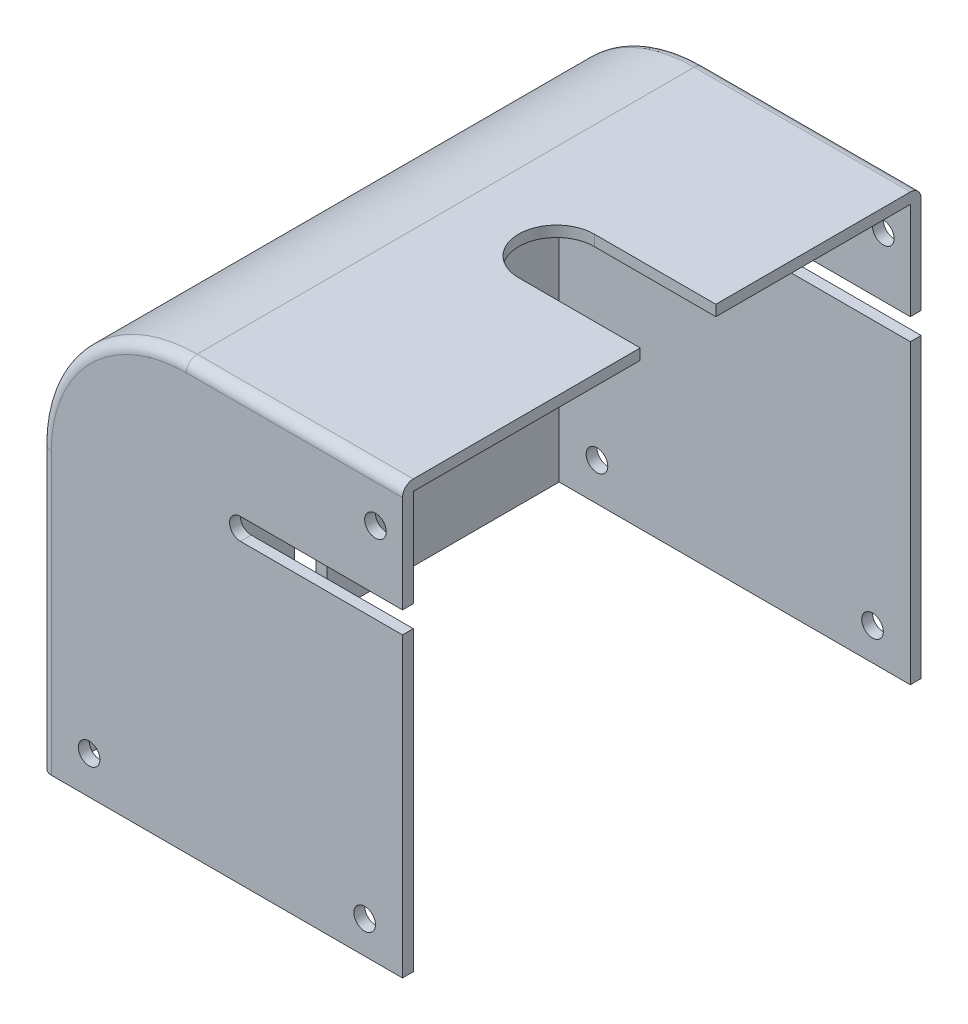
SolidWorks part; units mm, degrees
ref_plane "Front Plane" through (0, 0, 0) normal (0, 0, 1) x (1, 0, 0)
ref_plane "Top Plane" through (0, 0, 0) normal (0, 1, 0) x (1, 0, 0)
ref_plane "Right Plane" through (0, 0, 0) normal (1, 0, 0) x (0, 0, -1)
sketch "Sketch1" plane through (0, 0, 0) normal (0, 0, 1) x (1, 0, 0)
  line L0 (0, 0) -> (-40, 0)
  line L1 (-65, -25) -> (-65, -77)
  line L2 (0, 2) -> (-40, 2)
  line L3 (-67, -25) -> (-67, -77)
  line L4 (0, 0) -> (0, 2)
  line L5 (-65, -77) -> (-67, -77)
  arc A0 (-40, 0) -> (-65, -25) centre (-40, -25) ccw
  arc A1 (-40, 2) -> (-67, -25) centre (-40, -25) ccw
  dimension "D1" = 25
  dimension "D2" = 65
  dimension "D3" = 77
  dimension "D4" = 2
extrude "Boss-Extrude1" add sketch "Sketch1" along normal mid plane 92
sketch "Sketch2" plane through (0, 0, 46) normal (0, 0, 1) x (1, 0, 0)
  line L0 (-67, -25) -> (-67, -77) construction
  line L1 (0, 2) -> (-40, 2) construction
  line L2 (-67, -25) -> (-67, -77)
  line L3 (0, 2) -> (-40, 2)
  line L4 (-67, -77) -> (0, -77)
  line L5 (0, -77) -> (0, 2)
  arc A0 (-40, 2) -> (-67, -25) centre (-40, -25) ccw construction
  arc A1 (-40, 2) -> (-67, -25) centre (-40, -25) ccw
extrude "Boss-Extrude2" add sketch "Sketch2" along normal blind 2
mirror "Mirror1" about plane through (0, 0, 0) normal (0, 0, 1) of "Boss-Extrude2"
fillet "Fillet1" radius 2 6 edges at (-67, -51, -48) (-59.0919, -5.9081, -48) (-20, 2, -48) (-67, -51, 48) (-59.0919, -5.9081, 48) (-20, 2, 48)
sketch "Sketch3" plane through (-67, 0, 0) normal (-1, 0, 0) x (0, 0, 1)
  line L0 (0, -77) -> (0, -47) construction
  line L1 (46, -77) -> (-46, -77) construction
  line L2 (-3, -77) -> (-3, -47)
  line L3 (3, -77) -> (3, -47)
  arc A0 (-3, -77) -> (3, -77) centre (0, -77) ccw
  arc A1 (3, -47) -> (-3, -47) centre (0, -47) ccw
  point P4 (0, -62)
  dimension "D1" = 6
  dimension "D2" = 30
extrude "Cut-Extrude1" cut sketch "Sketch3" against normal blind 5
sketch "Sketch4" plane through (0, 0, 48) normal (0, 0, 1) x (1, 0, 0)
  line L0 (0, -20) -> (-30, -20) construction
  line L1 (0, -77) -> (0, 0) construction
  line L2 (0, -22) -> (-30, -22)
  line L3 (0, -18) -> (-30, -18)
  arc A0 (0, -22) -> (0, -18) centre (0, -20) ccw
  arc A1 (-30, -18) -> (-30, -22) centre (-30, -20) ccw
  point P4 (-15, -20)
  dimension "D1" = 20
  dimension "D2" = 4
  dimension "D3" = 30
extrude "Cut-Extrude2" cut sketch "Sketch4" against normal through all
sketch "Sketch5" plane through (0, 2, 0) normal (0, 1, 0) x (1, 0, 0)
  line L0 (0, 3) -> (-22.5, 3) construction
  line L2 (0, -4) -> (-22.5, -4)
  line L3 (0, 10) -> (-22.5, 10)
  line L4 (0, -46) -> (0, 46) construction
  line L5 (-40, 48) -> (0, 48) construction
  arc A0 (0, -4) -> (0, 10) centre (0, 3) ccw
  arc A1 (-22.5, 10) -> (-22.5, -4) centre (-22.5, 3) ccw
  point P2 (0, 4.6976)
  point P4 (-11.25, 3)
  dimension "D1" = 7
  dimension "D2" = 22.5
  dimension "D3" = 45
extrude "Cut-Extrude3" cut sketch "Sketch5" against normal through all
sketch "Sketch6" plane through (0, 0, 48) normal (0, 0, 1) x (1, 0, 0)
  line L0 (0, -18) -> (0, 0) construction
  line L1 (-65, -77) -> (0, -77) construction
  line L2 (0, -77) -> (0, -22) construction
  line L3 (-65, -25) -> (-65, -77) construction
  circle A0 centre (-5, -7) radius 2
  circle A1 centre (-7, -71) radius 2
  circle A2 centre (-58, -70) radius 2
  point P6 (-49.8312, -73.7742)
  point P7 (-5.7456, -73.7742)
  point P8 (-3.6431, -8.2067)
  dimension "D1" = 4
  dimension "D2" = 7
  dimension "D3" = 5
  dimension "D4" = 6
  dimension "D5" = 7
  dimension "D6" = 7
  dimension "D7" = 7
extrude "Cut-Extrude4" cut sketch "Sketch6" against normal through all
